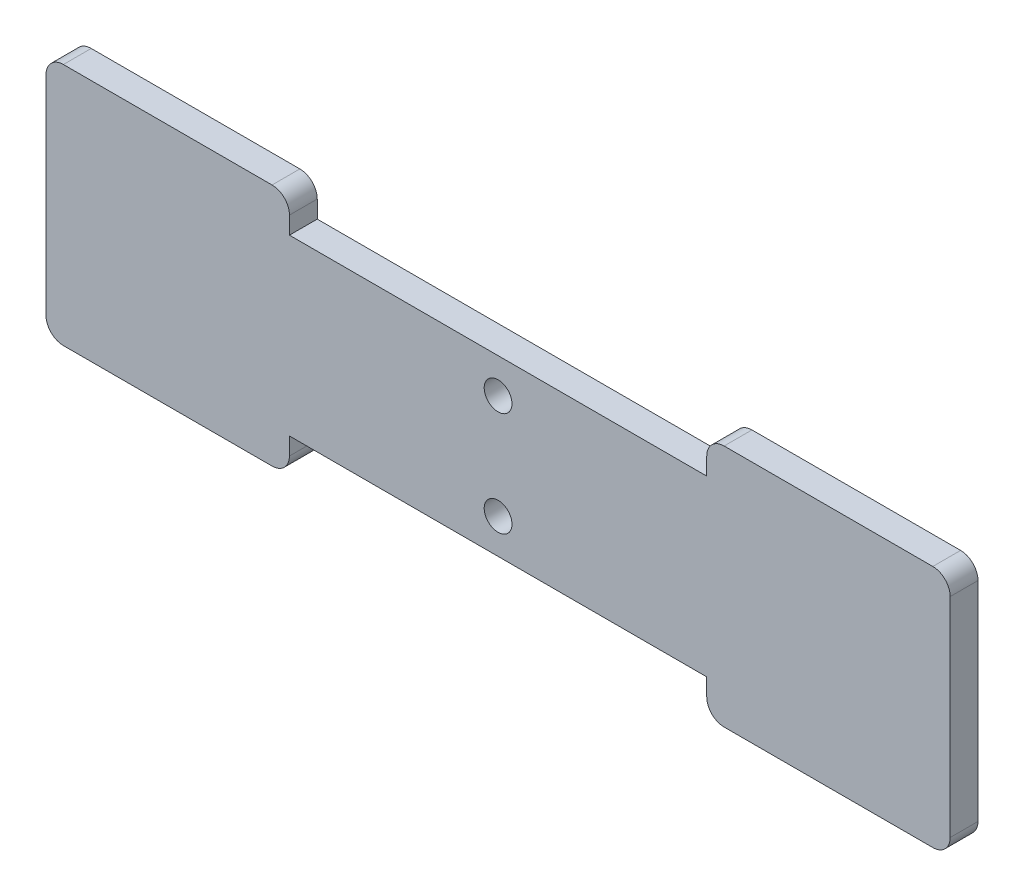
SolidWorks part; units mm, degrees
ref_plane "Front Plane" through (0, 0, 0) normal (0, 0, 1) x (1, 0, 0)
ref_plane "Top Plane" through (0, 0, 0) normal (0, 1, 0) x (1, 0, 0)
ref_plane "Right Plane" through (0, 0, 0) normal (1, 0, 0) x (0, 0, -1)
sketch "草图1" plane through (0, 0, 0) normal (0, 0, 1) x (1, 0, 0)
  line L1 (-26, 5) -> (26, 5)
  line L2 (-26, 5) -> (-26, -5)
  line L3 (-26, -5) -> (26, -5)
  line L4 (26, 5) -> (26, -5)
extrude "凸台-拉伸1" add sketch "草图1" along normal blind 1.6
sketch "草图2" plane through (0, 0, 0) normal (0, 0, 1) x (1, 0, 0)
  circle A0 centre (0, 3) radius 0.8
  circle A1 centre (0, -3) radius 0.8
extrude "切除-拉伸1" cut sketch "草图2" along normal blind 1.6
sketch "草图3" plane through (0, 0, 0) normal (0, 0, 1) x (1, 0, 0)
  line L1 (-26, 7) -> (-12, 7)
  line L2 (-26, 7) -> (-26, -7)
  line L3 (-26, -7) -> (-12, -7)
  line L4 (-12, 7) -> (-12, -7)
  line L9 (12, -7) -> (26, -7)
  line L10 (12, -7) -> (12, 7)
  line L11 (12, 7) -> (26, 7)
  line L12 (26, -7) -> (26, 7)
  point P4 (13.5734, -17.0185)
  point P5 (0, 0)
extrude "凸台-拉伸3" add sketch "草图3" along normal blind 1.6
fillet "圆角1" radius 1 8 edges at (-12, 7, 0.8) (12, 7, 0.8) (26, 7, 0.8) (26, -7, 0.8) (12, -7, 0.8) (-12, -7, 0.8) (-26, 7, 0.8) (-26, -7, 0.8)
